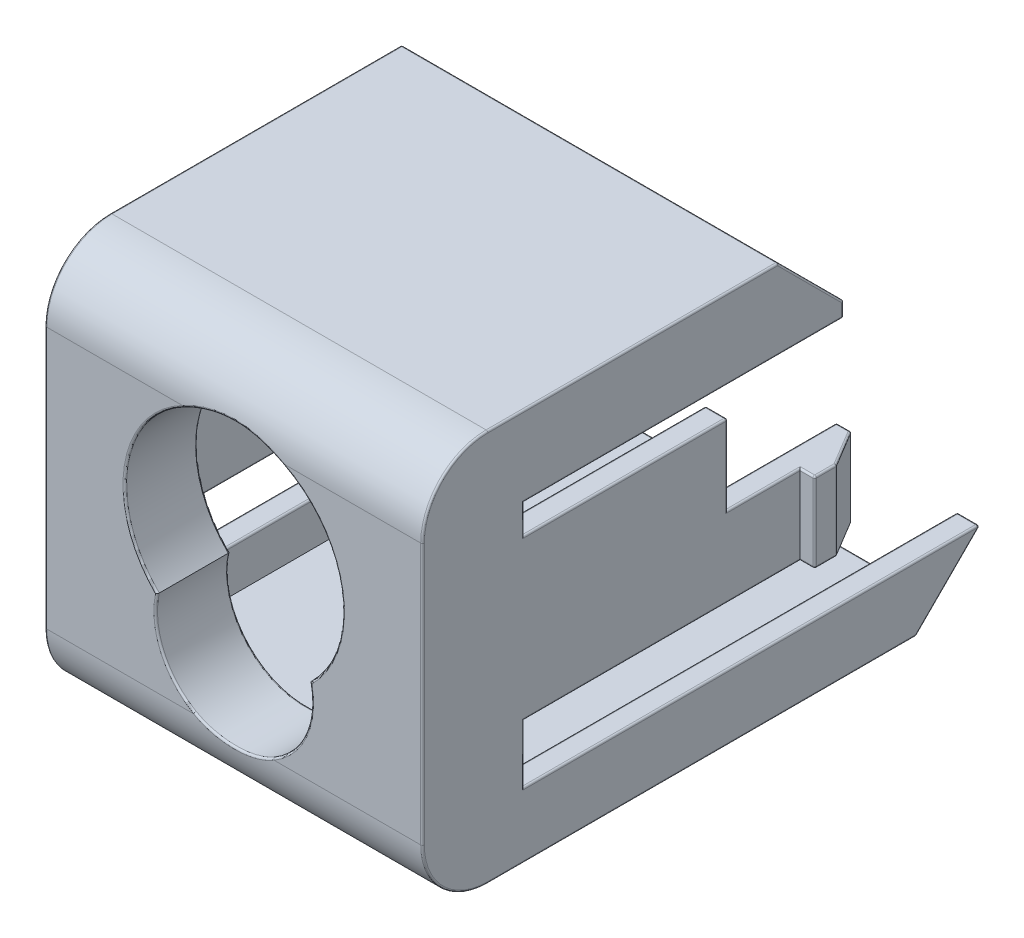
SolidWorks part; units mm, degrees
ref_plane "Front Plane" through (0, 0, 0) normal (0, 0, 1) x (1, 0, 0)
ref_plane "Top Plane" through (0, 0, 0) normal (0, 1, 0) x (1, 0, 0)
ref_plane "Right Plane" through (0, 0, 0) normal (1, 0, 0) x (0, 0, -1)
ref_plane "Plane1"
sketch "Sketch1" plane through (0, 0, 0) normal (1, 0, 0) x (0, 1, 0)
  line L0 (-10.8, -21.6) -> (-9.6, -22.8)
  line L1 (-9.6, -22.8) -> (-9.6, -10.8)
  line L2 (-9.6, -10.8) -> (-10.8, -10.8)
  line L3 (-10.8, -10.8) -> (-10.8, -21.6)
  line L4 (-10.8, 2) -> (-10.8, -10.8)
  line L5 (-10.8, -10.8) -> (-9.6, -10.8)
  line L6 (-9.6, -10.8) -> (-9.6, 4)
  line L7 (-9.6, 4) -> (9.36, 4)
  line L8 (9.36, 4) -> (9.36, -15.44)
  line L9 (9.36, -15.44) -> (10.8, -14)
  line L10 (10.8, -14) -> (10.8, 2)
  line L11 (7.2, 5.6) -> (-7.2, 5.6)
  line L12 (7.2, -17.6) -> (9.36, -15.44)
  line L13 (9.36, -15.44) -> (9.36, 4)
  line L14 (9.36, 4) -> (-9.6, 4)
  line L15 (-9.6, 4) -> (-9.6, -10.8)
  line L16 (-9.6, -10.8) -> (-9.6, -22.8)
  line L17 (-9.6, -22.8) -> (-7.2, -25.2)
  line L18 (-7.2, -25.2) -> (-7.2, 0)
  line L19 (-7.2, 0) -> (-4, 0)
  line L20 (-4, 0) -> (-4, -15.2)
  line L21 (-4, -15.2) -> (0.4, -15.2)
  line L22 (0.4, -15.2) -> (0.4, -11.2)
  line L23 (0.4, -11.2) -> (4.8, -11.2)
  line L24 (4.8, -11.2) -> (4.8, 0)
  line L25 (4.8, 0) -> (6.4, 0)
  line L26 (6.4, 0) -> (6.4, -17.6)
  line L27 (6.4, -17.6) -> (7.2, -17.6)
  arc A0 (10.8, 2) -> (7.2, 5.6) centre (7.2, 2) ccw
  arc A1 (-7.2, 5.6) -> (-10.8, 2) centre (-7.2, 2) ccw
  dimension "D2" = 3.6
  dimension "D1" = 21.6
  dimension "D3" = 135
  dimension "D4" = 5.6
  dimension "D5" = 45
  dimension "D6" = 3.6
  dimension "D7" = 4.4
  dimension "D8" = 4.4
  dimension "D9" = 4.4
  dimension "D10" = 0.8
  dimension "D11" = 135
  dimension "D12" = 1.6
  dimension "D13" = 16.8
  dimension "D14" = 20.8
  dimension "D15" = 1.44
  dimension "D16" = 1.2
  dimension "D17" = 1.6
  dimension "D18" = 135
extrude "Extrusion1" add sketch "Sketch1" along normal blind 10.4 and the other way blind 10.4 contours L2 L3 L0 L1 | L11 A1 L4 L2 L6 L7 L8 L9 L10 A0 | L26 L27 L12 L8 L7 L6 L1 L17 L18 L19 L20 L21 L22 L23 L24 L25
ref_plane "Plane2"
sketch "Sketch2" plane through (0, 0, 0) normal (1, 0, 0) x (0, 1, 0)
  line L0 (7.2, -17.6) -> (9.36, -15.44)
  line L1 (9.36, -15.44) -> (9.36, 4)
  line L2 (9.36, 4) -> (-9.6, 4)
  line L3 (-9.6, 4) -> (-9.6, -10.8)
  line L4 (-9.6, -10.8) -> (-9.6, -22.8)
  line L5 (-9.6, -22.8) -> (-7.2, -25.2)
  line L6 (-7.2, -25.2) -> (-7.2, 0)
  line L7 (-7.2, 0) -> (-4, 0)
  line L8 (-4, 0) -> (-4, -15.2)
  line L9 (-4, -15.2) -> (0.4, -15.2)
  line L10 (0.4, -15.2) -> (0.4, -11.2)
  line L11 (0.4, -11.2) -> (4.8, -11.2)
  line L12 (4.8, -11.2) -> (4.8, 0)
  line L13 (4.8, 0) -> (6.4, 0)
  line L14 (6.4, 0) -> (6.4, -17.6)
  line L15 (6.4, -17.6) -> (7.2, -17.6)
  line L19 (-10.8, 2) -> (-10.8, -21.6) construction
  line L20 (10.8, -14) -> (10.8, 2) construction
  line L21 (7.2, 5.6) -> (-7.2, 5.6) construction
  line L22 (7.2, 5.6) -> (-7.2, 5.6) construction
  line L23 (-10.8, 2) -> (-10.8, -21.6) construction
  dimension "D1" = 21.6
  dimension "D2" = 135
  dimension "D3" = 5.6
  dimension "D4" = 45
  dimension "D5" = 3.6
  dimension "D6" = 4.4
  dimension "D7" = 4.4
  dimension "D8" = 4.4
  dimension "D9" = 0.8
  dimension "D10" = 135
  dimension "D11" = 1.6
  dimension "D12" = 16.8
  dimension "D13" = 20.8
  dimension "D14" = 1.44
  dimension "D15" = 1.2
  dimension "D16" = 1.6
extrude "Extrusion2" cut sketch "Sketch2" against normal mid plane 18.4
ref_plane "Plane3"
sketch "Sketch3" plane through (0, 0, 0) normal (1, 0, 0) x (0, 1, 0)
  line L0 (-10.8, -21.6) -> (-9.6, -22.8)
  line L1 (-9.6, -22.8) -> (-9.6, -10.8)
  line L2 (-9.6, -10.8) -> (-10.8, -10.8)
  line L3 (-10.8, -10.8) -> (-10.8, -21.6)
  line L5 (-10.8, 2) -> (-10.8, -21.6) construction
  line L6 (10.8, -14) -> (10.8, 2) construction
  line L7 (-7.2, -25.2) -> (-7.2, 0) construction
  line L8 (7.2, 5.6) -> (-7.2, 5.6) construction
  line L9 (-7.2, 0) -> (-4, 0) construction
  line L10 (-10.8, -21.6) -> (-7.2, -25.2) construction
  line L11 (0.4, -15.2) -> (0.4, -11.2) construction
  line L12 (4.8, -11.2) -> (4.8, 0) construction
  line L13 (-4, 0) -> (-4, -15.2) construction
  line L14 (6.4, 0) -> (6.4, -17.6) construction
  line L15 (6.4, -17.6) -> (7.2, -17.6) construction
  line L16 (0.4, -11.2) -> (4.8, -11.2) construction
  line L17 (-4, -15.2) -> (0.4, -15.2) construction
  dimension "D1" = 21.6
  dimension "D2" = 270
  dimension "D3" = 5.6
  dimension "D4" = 45
  dimension "D5" = 3.6
  dimension "D6" = 4.4
  dimension "D7" = 4.4
  dimension "D8" = 4.4
  dimension "D9" = 23.2
  dimension "D10" = 1.6
  dimension "D11" = 16.8
  dimension "D12" = 20.8
  dimension "D13" = 90
extrude "Extrusion5" cut sketch "Sketch3" against normal mid plane 8
sketch "Sketch4" plane through (0, 0.4, 0) normal (0, 1, 0) x (-1, 0, 0)
  line L0 (-9.2, -15.2) -> (-10.4, -15.2)
  line L1 (-10.4, -15.2) -> (-11.2, -15.2)
  line L2 (-11.2, -15.2) -> (-11.2, -16.4)
  line L3 (-11.2, -16.4) -> (-10, -18.4)
  line L4 (-10, -18.4) -> (-9.2, -18.4)
  line L5 (-9.2, -18.4) -> (-9.2, -15.2)
  line L6 (10.4, -15.2) -> (10.4, -11.2)
  line L7 (10.4, -11.2) -> (9.2, -11.2)
  line L8 (9.2, -11.2) -> (9.2, -15.2)
  line L9 (9.2, -15.2) -> (10.4, -15.2)
extrude "Extrusion6" add sketch "Sketch4" against normal up to surface (4.4 mm away) up to face at (-9.8, -4, -7.6)
sketch "Sketch5" plane through (0, 0, 5.6) normal (0, 0, 1) x (1, 0, 0)
  arc A0 (4.2012, -2.4837) -> (-4.2012, -2.4837) centre (0, 1.8) ccw
  arc A1 (-4.2012, -2.4837) -> (4.2012, -2.4837) centre (0, -3.4) ccw
  dimension "D1" = 12
  dimension "D2" = 8.6
  dimension "D3" = 5.2
extrude "Extrusion8" cut sketch "Sketch5" against normal through all
sketch "Sketch6" plane through (0, 0, 4) normal (0, 0, -1) x (-1, 0, 0)
  arc A0 (5.157, -3.2245) -> (-5.157, -3.2245) centre (0, 1.8) ccw
  arc A1 (-5.157, -3.2245) -> (5.157, -3.2245) centre (0, -3.4) ccw
  arc A2 (-4.2012, -2.4837) -> (4.2012, -2.4837) centre (0, -3.4) ccw
  arc A3 (4.2012, -2.4837) -> (-4.2012, -2.4837) centre (0, 1.8) ccw
extrude "Extrusion9" add sketch "Sketch6" along normal blind 2.4
fillet "Fillet1" radius 0.1 96 edges at (0, 9, 1.6) (0, -8.56, 1.6) (0, 7.8, 1.6) (0, -7.7, 1.6) (3.9004, -5.2101, 5.6) (-3.9004, -5.2101, 5.6) (-5.9211, 2.7697, 5.6) (5.9211, 2.7697, 5.6) (0.8749, 7.7359, 5.5599) (-0.6445, -7.6514, 5.5716) (9.6, -4, -18.4) (9.6, 0.4, -18.4) (9.2, 0.4, -14.8) (10.8, 0.4, -15.2) (10.8, -4, -15.2) (11.2, -4, -15.8) (11.2, 0.4, -15.8) (11.2, -1.8, -15.2) (9.2, 4.8, -5.6) (9.8, 4.8, -11.2) (-9.8, 4.8, -11.2) (-10.4, 2.6, -11.2) (9.2, 5.6, 0) (10.4, -4, -7.6) (-10.4, 4.8, -5.6) (6.6, -9.6, -22.8) (10.4, -5.6, 0) (-9.2, -4, -7.6) (0, 9.36, -15.44) (-10.4, 5.6, 0) (9.2, 6.8, -17.6) (9.2, 8.28, -16.52) (9.8, 6.4, -17.6) (9.8, -7.2, -25.2) (10.4, -7.2, -12.6) (-9.2, -5.6, 0) (-9.8, 6.4, -17.6) (-10.4, 6.4, -8.8) (9.8, 7.2, -17.6) (7.2, -10.8, -21.6) (10.4, -9, -23.4) (-9.2, -7.2, -12.6) (-9.2, -8.4, -24) (-9.8, 7.2, -17.6) (-10.4, 6.8, -17.6) (-9.8, -7.2, -25.2) (0, 10.8, -14) (-10.4, 9, -15.8) (-7.2, -10.8, -21.6) (-10.4, -10.8, -9.8) (-10.4, -9.7456, 4.5456) (-10.4, 0, 5.6) (-10.4, 9.7456, 4.5456) (-10.4, 10.8, -6) (-10.4, -9, -23.4) (-10.4, -7.2, -12.6) (-4, -10.2, -22.2) (-4, -10.8, -16.2) (10.4, 10.8, -6) (10.4, 9.7456, 4.5456) (10.4, 0, 5.6) (10.4, -9.7456, 4.5456) (10.4, -10.8, -9.8) (10.4, 9, -15.8) (-10.4, -5.6, 0) (0, -10.8, -10.8) (-6.6, -9.6, -22.8) (-4, -9.6, -16.8) (10.4, 6.8, -17.6) (-9.2, 8.28, -16.52) (-9.2, 6.8, -17.6) (4, -10.8, -16.2) (0, -9.6, -10.8) (4, -10.2, -22.2) (10.4, 6.4, -8.8) (-9.2, 6.4, -8.8) (4, -9.6, -16.8) (9.2, -8.4, -24) (9.2, -7.2, -12.6) (10.4, 5.6, 0) (9.2, 6.4, -8.8) (-9.2, 5.6, 0) (9.2, -5.6, 0) (10.4, 4.8, -5.6) (-9.2, 4.8, -5.6) (9.2, -4, -9.2) (10.4, 2.6, -11.2) (-9.2, 2.6, -11.2) (9.2, -1.8, -18.4) (10.4, 0.4, -13.2) (9.2, 2.6, -11.2) (-9.2, 0.4, -13.2) (10.6, -4, -17.4) (10.6, 0.4, -17.4) (11.2, -1.8, -16.4) (10, -1.8, -18.4)
